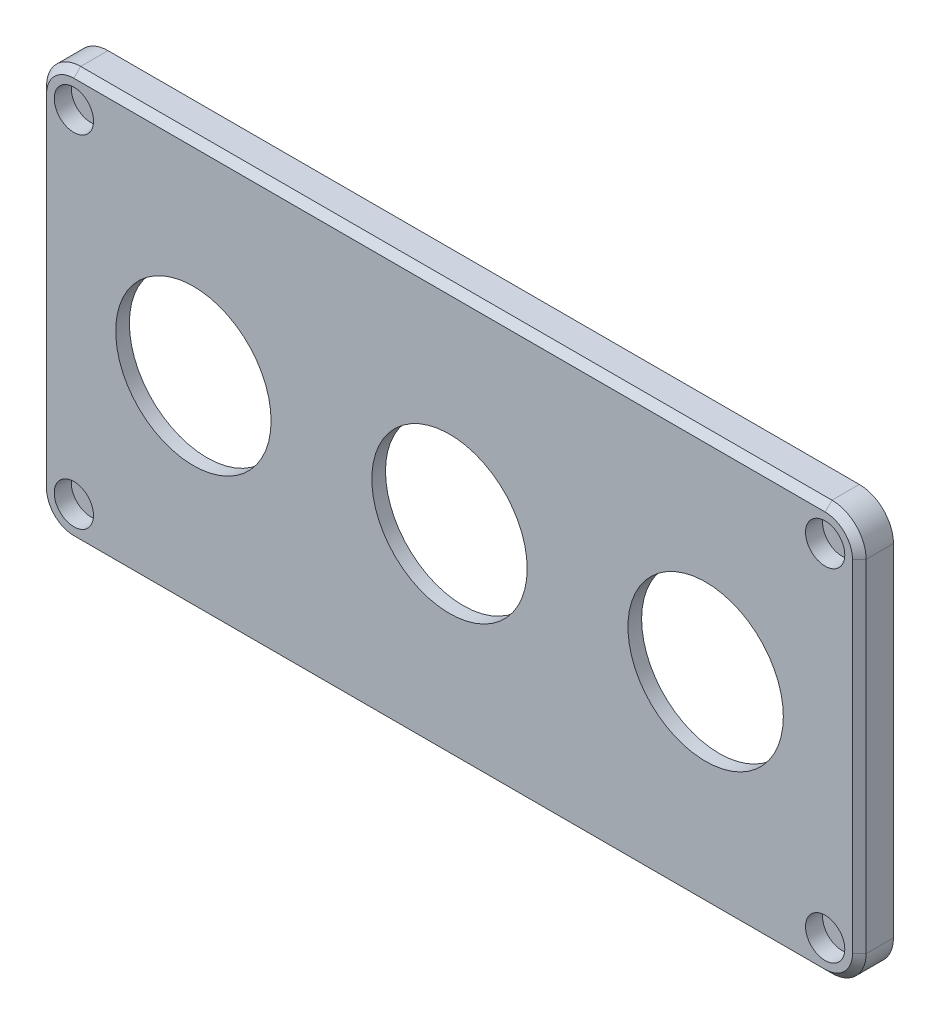
SolidWorks part; units mm, degrees
ref_plane "Front Plane" through (0, 0, 0) normal (0, 0, 1) x (1, 0, 0)
ref_plane "Top Plane" through (0, 0, 0) normal (0, 1, 0) x (1, 0, 0)
ref_plane "Right Plane" through (0, 0, 0) normal (1, 0, 0) x (0, 0, -1)
sketch "Sketch1" plane through (0, 0, 0) normal (0, 0, 1) x (1, 0, 0)
  line L1 (-60, 30) -> (60, 30)
  line L2 (-60, 30) -> (-60, -30)
  line L3 (-60, -30) -> (60, -30)
  line L4 (60, 30) -> (60, -30)
  line L5 (-60, 30) -> (60, -30) construction
  line L6 (-60, -30) -> (60, 30) construction
  point P0 (0, 0)
  dimension "D1" = 120
  dimension "D2" = 60
extrude "Boss-Extrude1" add sketch "Sketch1" along normal blind 5
sketch "Sketch2" plane through (0, 0, 5) normal (0, 0, 1) x (1, 0, 0)
  circle A0 centre (0, 0) radius 11.375
  circle A1 centre (37.5, 0) radius 11.375
  circle A2 centre (-37.5, 0) radius 11.375
  dimension "D3" = 22.75
  dimension "D1" = 75
  dimension "D2" = 37.5
extrude "Cut-Extrude1" cut sketch "Sketch2" against normal through all
fillet "Fillet1" radius 5 4 edges at (-60, -30, 2.5) (60, -30, 2.5) (60, 30, 2.5) (-60, 30, 2.5)
sketch "Sketch3" plane through (0, 0, 5) normal (0, 0, 1) x (1, 0, 0)
  circle A0 centre (-55, 25) radius 1.5
  circle A1 centre (55, 25) radius 1.5
  circle A2 centre (55, -25) radius 1.5
  circle A3 centre (-55, -25) radius 1.5
  dimension "D1" = 3
extrude "Cut-Extrude2" cut sketch "Sketch3" against normal through all
sketch "Sketch4" plane through (0, 0, 5) normal (0, 0, 1) x (1, 0, 0)
  circle A0 centre (-55, 25) radius 2.875
  circle A1 centre (55, 25) radius 2.875
  circle A2 centre (55, -25) radius 2.875
  circle A3 centre (-55, -25) radius 2.875
  dimension "D1" = 5.75
extrude "Cut-Extrude3" cut sketch "Sketch4" against normal blind 2.5
chamfer "Chamfer1" distance 1 angle 45 8 edges at (0, -30, 5) (58.5355, -28.5355, 5) (-58.5355, -28.5355, 5) (60, 0, 5) (-60, 0, 5) (58.5355, 28.5355, 5) (-58.5355, 28.5355, 5) (0, 30, 5)
sketch "Sketch5" plane through (0, 0, 0) normal (0, 0, -1) x (-1, 0, 0)
  circle A0 centre (-37.5, 0) radius 16
  circle A1 centre (0, 0) radius 16
  circle A2 centre (37.5, 0) radius 16
  dimension "D1" = 32
extrude "Cut-Extrude4" cut sketch "Sketch5" against normal blind 3
sketch "Sketch6" plane through (0, 0, 2.5) normal (0, 0, 1) x (1, 0, 0)
  circle A0 centre (-55, 25) radius 2.5
  circle A1 centre (55, 25) radius 2.5
  circle A2 centre (55, -25) radius 2.5
  circle A3 centre (-55, -25) radius 2.5
  dimension "D1" = 5
extrude "Boss-Extrude2" add sketch "Sketch6" against normal blind 0.15
